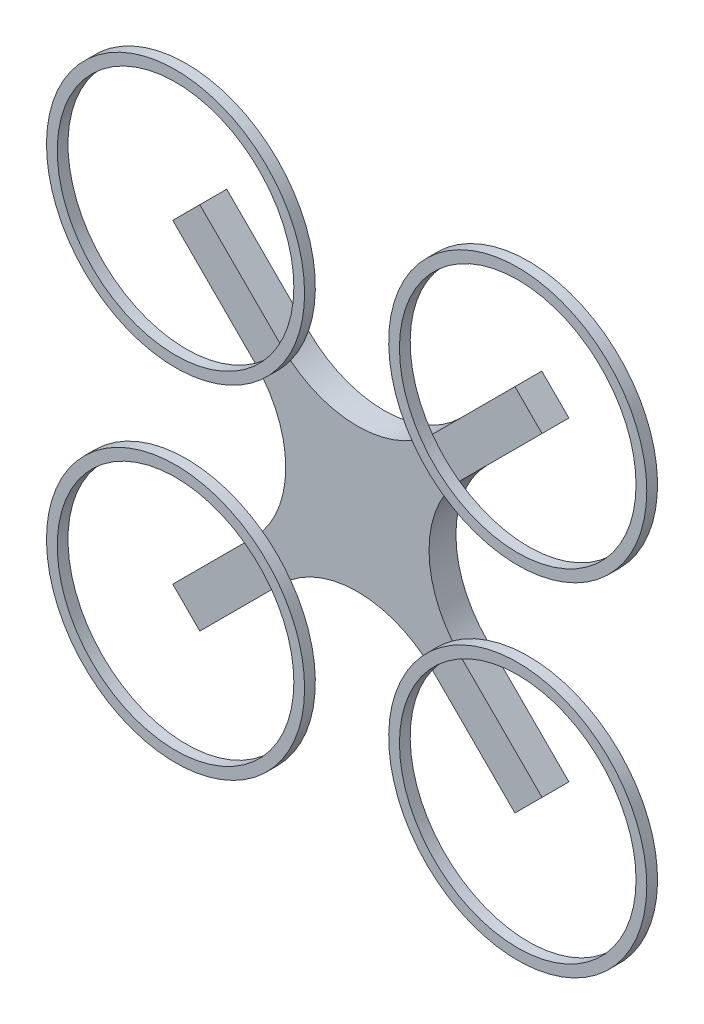
SolidWorks part; units mm, degrees
ref_plane "Front Plane" through (0, 0, 0) normal (0, 0, 1) x (1, 0, 0)
ref_plane "Top Plane" through (0, 0, 0) normal (0, 1, 0) x (1, 0, 0)
ref_plane "Right Plane" through (0, 0, 0) normal (1, 0, 0) x (0, 0, -1)
sketch "Sketch2" plane through (0, 0, 0) normal (0, 0, 1) x (1, 0, 0)
  line L0 (0, 0) -> (31.8198, 31.8198) construction
  line L1 (0, 0) -> (31.8198, 0) construction
  line L2 (0, 0) -> (0, 31.8198) construction
  line L3 (0, 31.8198) -> (31.8198, 31.8198) construction
  line L4 (31.8198, 0) -> (31.8198, 31.8198) construction
  line L5 (0, 5.0395) -> (29.3001, 34.3395)
  line L6 (29.3001, 34.3395) -> (34.3395, 29.3001)
  line L7 (34.3395, 29.3001) -> (5.0395, 0)
  line L8 (34.3395, -29.3001) -> (5.0395, 0)
  line L9 (29.3001, -34.3395) -> (34.3395, -29.3001)
  line L10 (0, -5.0395) -> (29.3001, -34.3395)
  line L11 (0, -5.0395) -> (-29.3001, -34.3395)
  line L12 (-29.3001, -34.3395) -> (-34.3395, -29.3001)
  line L13 (-34.3395, -29.3001) -> (-5.0395, 0)
  line L14 (-34.3395, 29.3001) -> (-5.0395, 0)
  line L15 (-29.3001, 34.3395) -> (-34.3395, 29.3001)
  line L16 (0, 5.0395) -> (-29.3001, 34.3395)
  dimension "D1" = 45
extrude "Boss-Extrude1" add sketch "Sketch2" along normal blind 5
fillet "Fillet1" radius 20 4 edges at (-5.0395, 0, 2.5) (0, -5.0395, 2.5) (5.0395, 0, 2.5) (0, 5.0395, 2.5)
sketch "Sketch3" plane through (0, 0, 5) normal (0, 0, 1) x (1, 0, 0)
  line L0 (-29.3001, 34.3395) -> (-34.3395, 29.3001) construction
  line L1 (34.3395, 29.3001) -> (29.3001, 34.3395) construction
  line L2 (29.3001, -34.3395) -> (34.3395, -29.3001) construction
  line L3 (-34.3395, -29.3001) -> (-29.3001, -34.3395) construction
  circle A0 centre (-31.8198, 31.8198) radius 22
  circle A1 centre (31.8198, 31.8198) radius 22
  circle A2 centre (31.8198, -31.8198) radius 22
  circle A3 centre (-31.8198, -31.8198) radius 22
  circle A4 centre (-31.8198, 31.8198) radius 24
  circle A5 centre (31.8198, 31.8198) radius 24
  circle A6 centre (31.8198, -31.8198) radius 24
  circle A7 centre (-31.8198, -31.8198) radius 24
  dimension "D1" = 44
  dimension "D2" = 2
extrude "Boss-Extrude2" add sketch "Sketch3" along normal blind 2
